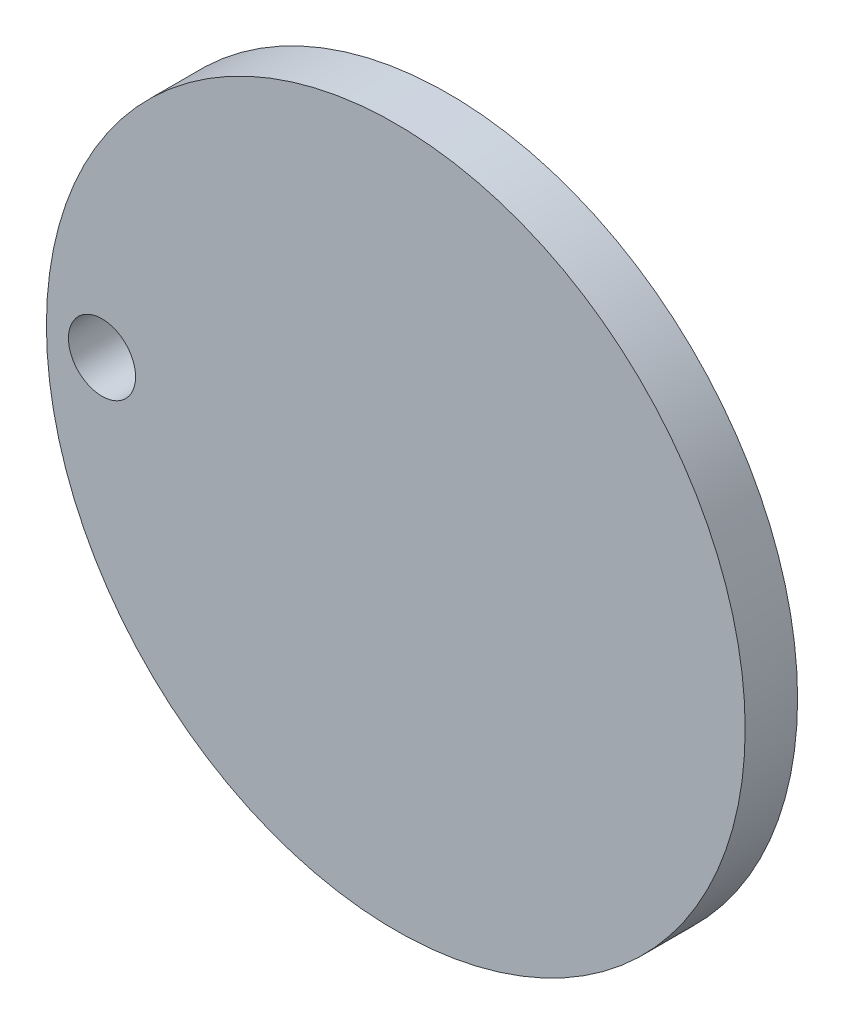
SolidWorks part; units mm, degrees
ref_plane "Plan de face" through (0, 0, 0) normal (0, 0, 1) x (1, 0, 0)
ref_plane "Plan de dessus" through (0, 0, 0) normal (0, 1, 0) x (1, 0, 0)
ref_plane "Plan de droite" through (0, 0, 0) normal (1, 0, 0) x (0, 0, -1)
sketch "Esquisse1" plane through (0, 0, 0) normal (0, 0, 1) x (1, 0, 0)
  circle A0 centre (0, 0) radius 20
  circle A1 centre (-16.817, 0) radius 1.9212
  dimension "D1" = 40
extrude "Boss.-Extru.1" add sketch "Esquisse1" along normal blind 3
